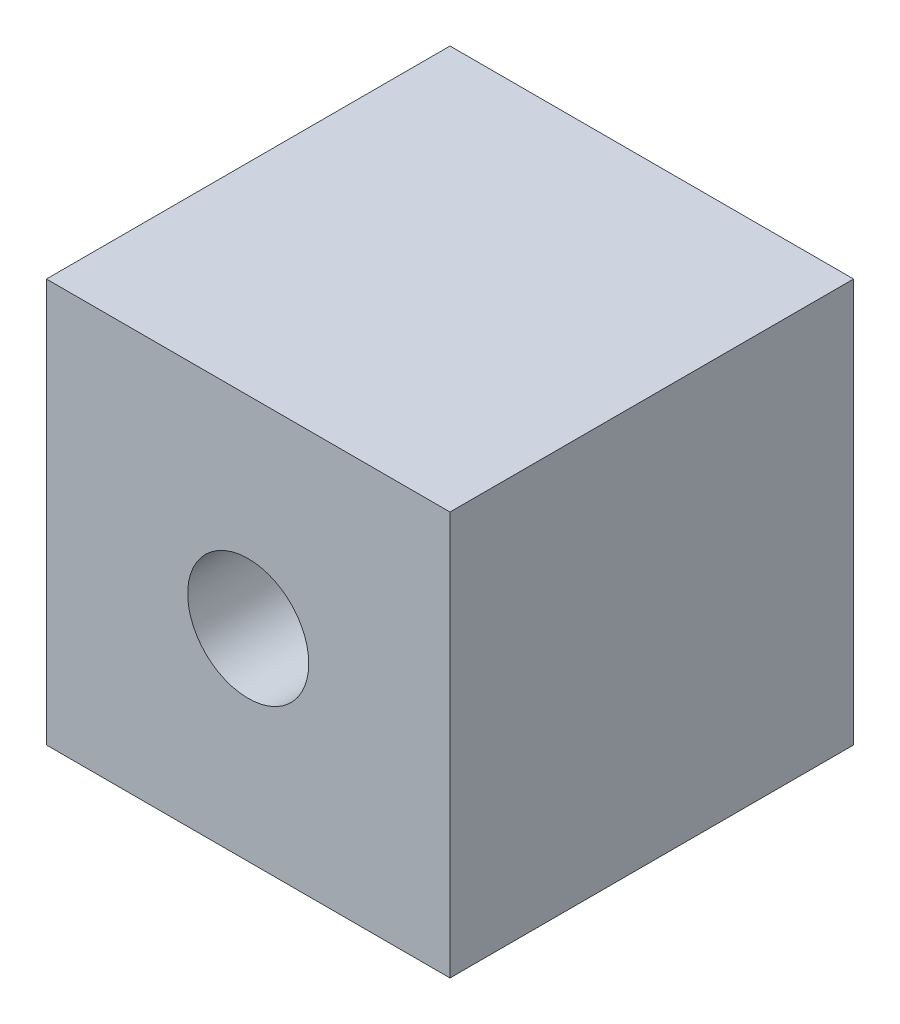
SolidWorks part; units mm, degrees
ref_plane "Front Plane" through (0, 0, 0) normal (0, 0, 1) x (1, 0, 0)
ref_plane "Top Plane" through (0, 0, 0) normal (0, 1, 0) x (1, 0, 0)
ref_plane "Right Plane" through (0, 0, 0) normal (1, 0, 0) x (0, 0, -1)
sketch "Sketch1" plane through (0, 0, 0) normal (0, 0, 1) x (1, 0, 0)
  line L1 (0, 0) -> (10, 0)
  line L2 (0, 0) -> (0, 10)
  line L3 (0, 10) -> (10, 10)
  line L4 (10, 0) -> (10, 10)
extrude "Boss-Extrude1" add sketch "Sketch1" along normal blind 10
sketch "Sketch2" plane through (0, 0, 10) normal (0, 0, 1) x (1, 0, 0)
  circle A0 centre (5, 5) radius 1.5
extrude "Cut-Extrude1" cut sketch "Sketch2" against normal through all
